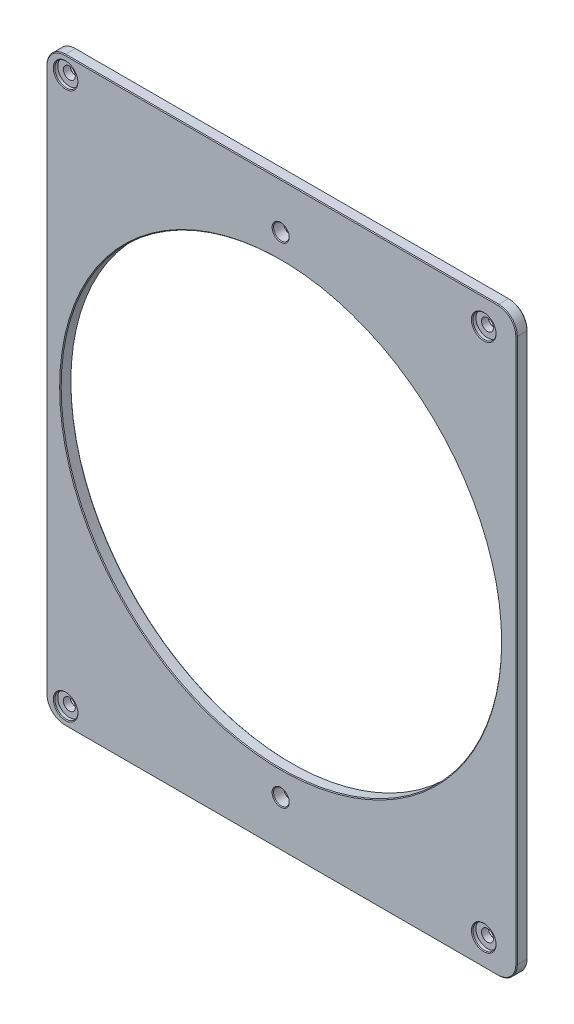
SolidWorks part; units mm, degrees
ref_plane "Front Plane" through (0, 0, 0) normal (0, 0, 1) x (1, 0, 0)
ref_plane "Top Plane" through (0, 0, 0) normal (0, 1, 0) x (1, 0, 0)
ref_plane "Right Plane" through (0, 0, 0) normal (1, 0, 0) x (0, 0, -1)
other "Configuration Table"
sketch "草图1" plane through (0, 0, 0) normal (0, 0, 1) x (1, 0, 0)
  line L0 (62.3, -78) -> (-53.9, -78)
  line L1 (67.3, -73) -> (67.3, 73)
  line L2 (62.3, 78) -> (-53.9, 78)
  line L3 (-58.9, -73) -> (-58.9, 73)
  line L4 (-57.3743, 76.5957) -> (-50.0357, 70.1007) construction
  line L5 (65.8355, 76.5355) -> (51.1514, 65.3931) construction
  line L6 (4, 0) -> (67.3, 0) construction
  circle A0 centre (4, 0) radius 59.1
  arc A1 (67.3, -73) -> (62.3, -78) centre (62.3, -73) cw
  arc A2 (-53.9, -78) -> (-58.9, -73) centre (-53.9, -73) cw
  arc A3 (67.3, 73) -> (62.3, 78) centre (62.3, 73) ccw
  arc A4 (-53.9, 78) -> (-58.9, 73) centre (-53.9, 73) ccw
  circle A7 centre (58.4934, 70.9643) radius 1.6
  circle A10 centre (-53.705, 73.3482) radius 1.6
  arc A11 (51.1, 64.5) -> (42.5, 75.1) centre (41.5, 65.5) ccw construction
  circle A12 centre (58.4934, -70.9643) radius 1.6
  circle A13 centre (-53.705, -73.3482) radius 1.6
  dimension "D1" = 118.2
extrude "凸台-拉伸1" add sketch "草图1" along normal blind 3
sketch "草图2" plane through (0, 0, 3) normal (0, 0, 1) x (1, 0, 0)
  line L0 (4, -59.1) -> (4, -72.2) construction
  line L1 (4, 59.1) -> (4, 72.2) construction
  circle A0 centre (4, -65.65) radius 2.1
  circle A1 centre (4, 65.65) radius 2.1
extrude "切除-拉伸1" cut sketch "草图2" against normal through all
sketch "草图3" plane through (0, 0, 3) normal (0, 0, 1) x (1, 0, 0)
  line L0 (4, 0) -> (16.8126, 0) construction
  circle A0 centre (58.4934, -70.9643) radius 3.1
  circle A1 centre (-53.705, -73.3482) radius 3.1
  circle A2 centre (-53.705, 73.3482) radius 3.1
  circle A3 centre (58.4934, 70.9643) radius 3.1
extrude "切除-拉伸2" cut sketch "草图3" against normal blind 1
chamfer "倒角1" distance 0.2 angle 45 30 edges at (63.1, 0, 3) (4.2, -78, 3) (-57.4355, -76.5355, 3) (-58.9, 0, 3) (-57.4355, 76.5355, 3) (4.2, 78, 3) (65.8355, 76.5355, 3) (67.3, 0, 3) (65.8355, -76.5355, 3) (6.1, 65.65, 3) (6.1, -65.65, 3) (61.5934, -70.9643, 3) (-50.605, -73.3482, 3) (-56.805, 73.3482, 3) (55.3934, 70.9643, 3) (-55.305, -73.3482, 0) (56.8934, -70.9643, 0) (63.1, 0, 0) (67.3, 0, 0) (65.8355, 76.5355, 0) (4.2, 78, 0) (-57.4355, 76.5355, 0) (-58.9, 0, 0) (-57.4355, -76.5355, 0) (4.2, -78, 0) (65.8355, -76.5355, 0) (60.0934, 70.9643, 0) (-52.105, 73.3482, 0) (6.1, 65.65, 0) (6.1, -65.65, 0)
